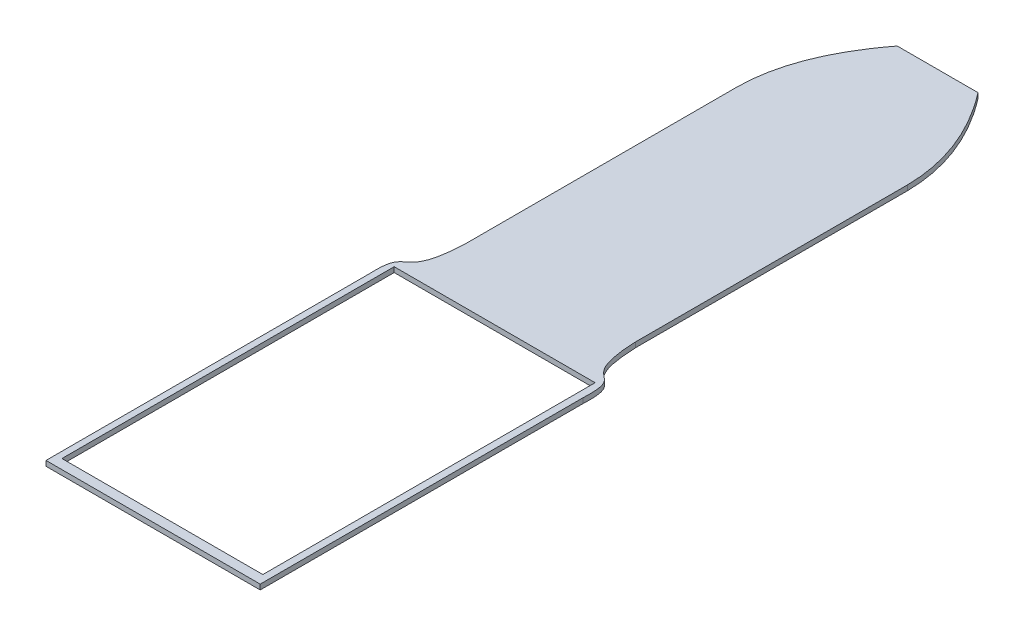
SolidWorks part; units mm, degrees
ref_plane "Front Plane" through (0, 0, 0) normal (0, 0, 1) x (1, 0, 0)
ref_plane "Top Plane" through (0, 0, 0) normal (0, 1, 0) x (1, 0, 0)
ref_plane "Right Plane" through (0, 0, 0) normal (1, 0, 0) x (0, 0, -1)
sketch "Sketch1" plane through (0, 0, 0) normal (0, -1, 0) x (-1, 0, 0)
  line L9 (-68.229, -80.901) -> (-68.229, 14.099)
  line L10 (-61.729, 35.9991) -> (-61.729, 115.9991)
  line L11 (-5.229, -80.901) -> (-5.229, 14.099)
  line L17 (-24.8578, 149.8289) -> (-48.6002, 149.8289)
  line L18 (-11.729, 35.9991) -> (-11.729, 115.9991)
  line L19 (-68.229, -80.901) -> (-5.229, -80.901)
  spline S0 degree 4 poles (-61.729, 35.9991) (-62.4215, 17.9336) (-67.5442, 25.0811) (-68.5403, 21.1592) (-68.229, 14.099) knots 0 0 0 0 0 1 1 1 1 1
  spline S1 degree 4 poles (-11.729, 35.9991) (-11.0365, 17.9336) (-5.9138, 25.0811) (-4.9177, 21.1592) (-5.229, 14.099) knots 0 0 0 0 0 1 1 1 1 1
  spline S2 degree 3 poles (-11.729, 115.9991) (-11.8683, 128.7119) (-17.3932, 140.1407) (-24.8578, 149.8289) knots 0 0 0 0 1 1 1 1
  spline S3 degree 3 poles (-61.729, 115.9991) (-61.5897, 128.7119) (-56.0648, 140.1407) (-48.6002, 149.8289) knots 0 0 0 0 1 1 1 1
  point P33 (-36.729, 149.8289)
  dimension "D1" = 95
  dimension "D2" = 80
extrude "Boss-Extrude1" add sketch "Sketch1" along normal blind 1.5 contours L11 S1 L18 S2 L17 S3 L10 S0 L9 L19
sketch "Sketch2" plane through (0, 0, 0) normal (0, 1, 0) x (1, 0, 0)
  line L0 (36.729, -80.901) -> (36.729, 149.8289) construction
  line L1 (68.229, -80.901) -> (5.229, -80.901) construction
  line L2 (24.8578, 149.8289) -> (48.6002, 149.8289) construction
  point P6 (0, 0)
ref_plane "Plane1" through (37.2492, 12.1282, -76.2334) normal (1, 0, 0) x (0, 0, -1)
ref_plane "Plane2" through (36.729, 0, 0) normal (1, 0, 0) x (0, 0, -1)
sketch "Sketch6" plane through (36.729, 0, 0) normal (1, 0, 0) x (0, 0, -1)
  line L0 (-311.9659, -1.5) -> (150.1639, -1.5) construction
  line L3 (-80.901, -1.5) -> (-80.901, -31.2379) construction
  line L4 (-80.901, -31.2379) -> (-59.344, -24.3435) construction
  line L5 (-59.344, -24.3435) -> (-3.1998, 14.8059) construction
  line L6 (-3.1998, 14.8059) -> (64.8448, -4.4458) construction
  line L7 (64.8448, -4.4458) -> (76.7941, -9.7566) construction
  line L8 (76.7941, -9.7566) -> (52.285, -33.2558) construction
  line L9 (52.285, -33.2558) -> (90.1548, -40.1862) construction
  line L10 (90.1548, -40.1862) -> (110.6986, -30.7806) construction
  line L11 (110.6986, -30.7806) -> (124.8069, -10.7319) construction
  line L12 (124.8069, -10.7319) -> (128.2424, -10.0885) construction
  line L13 (128.2424, -10.0885) -> (144.0541, -7.888) construction
  line L15 (144.0541, -7.888) -> (149.8289, -6.5571) construction
  line L17 (149.8289, -6.5571) -> (149.8289, -1.5) construction
  spline_without_curve S0
  spline S1 degree 2 poles (144.0541, -7.888) (149.8289, -6.5571) (149.8289, -1.5) knots 0 0 0 1 1 1
  point P2 (-66.6049, -16.7435)
  point P3 (15.6149, -9.0496)
  point P5 (94.0625, -25.8126)
  point P23 (-310.7247, -1.5)
  point P33 (-80.901, -1.5)
ref_plane "Plane3" through (0, 0, 66.6049) normal (0, 0, 1) x (1, 0, 0)
sketch "Sketch8" plane through (0, 0, 66.6049) normal (0, 0, 1) x (1, 0, 0)
  line L0 (5.229, -1.5) -> (5.229, -16.7435) construction
  line L1 (5.229, -16.7435) -> (36.729, -16.7435) construction
  line L2 (36.729, -31.7831) -> (36.729, 32.0033) construction
  spline S0 degree 2 poles (5.229, -1.5) (5.229, -16.7435) (36.729, -16.7435) knots 0 0 0 1 1 1
ref_plane "Plane4" through (0, 0, -15.6149) normal (0, 0, 1) x (1, 0, 0)
sketch "Sketch9" plane through (0, 0, -15.6149) normal (0, 0, 1) x (1, 0, 0)
  line L0 (5.1858, -1.5) -> (5.1858, -10.0945) construction
  line L1 (5.1858, -10.0945) -> (36.729, -9.0496) construction
  line L2 (36.6851, -19.5058) -> (36.6851, 6.741) construction
  spline S0 degree 2 poles (5.1858, -1.5) (5.1858, -10.0945) (36.729, -9.0496) knots 0 0 0 1 1 1
ref_plane "Plane5" through (0, 0, -94.0625) normal (0, 0, 1) x (1, 0, 0)
sketch "Sketch10" plane through (0, 0, -94.0625) normal (0, 0, 1) x (1, 0, 0)
  line L0 (11.729, -1.5) -> (11.729, -14.2215) construction
  line L1 (11.729, -14.2215) -> (19.3823, -27.1444) construction
  line L2 (19.3823, -27.1444) -> (28.5985, -23.3803) construction
  line L3 (28.5985, -23.3803) -> (26.9057, -25.8126) construction
  line L4 (26.9057, -25.8126) -> (36.729, -25.8126) construction
  line L5 (36.729, -63.5804) -> (36.729, 11.9552) construction
  spline_without_curve S0
  point P15 (36.729, -25.8126)
ref_plane "Plane6" through (0, 0, -144.0541) normal (0, 0, 1) x (1, 0, 0)
sketch "Sketch11" plane through (0, 0, -144.0541) normal (0, 0, 1) x (1, 0, 0)
  line L0 (36.729, 10.3711) -> (36.729, -26.1472) construction
  line L1 (20.7937, -1.5) -> (20.7937, -5.3294) construction
  line L2 (20.7937, -5.3294) -> (29.7132, -7.888) construction
  line L3 (29.7132, -7.888) -> (36.729, -7.888) construction
  spline S0 degree 3 poles (20.7937, -1.5) (20.7937, -5.3294) (29.7132, -7.888) (36.729, -7.888) knots 0 0 0 0 1 1 1 1
  point P8 (36.729, -7.888)
sketch3d "3DSketch1"
  line L0 (68.229, -1.5, 80.901) -> (68.229, -1.5, -14.099) construction
  line L1 (61.729, -1.5, -35.9991) -> (61.729, -1.5, -115.9991) construction
  line L2 (68.229, -1.5, 80.901) -> (68.229, -1.5, -14.099)
  line L3 (61.729, -1.5, -35.9991) -> (61.729, -1.5, -115.9991)
  line L10 (68.229, -1.5, 80.901) -> (5.229, -1.5, 80.901)
  line L11 (5.229, -1.5, 80.901) -> (5.229, -1.5, -14.099)
  line L12 (11.729, -1.5, -35.9991) -> (11.729, -1.5, -115.9991)
  line L13 (24.8578, -1.5, -149.8289) -> (48.6002, -1.5, -149.8289)
  line L14 (61.729, -1.5, -115.9991) -> (61.729, -1.5, -35.9991)
  line L15 (68.229, -1.5, -14.099) -> (68.229, -1.5, 80.901)
  line L16 (68.229, -1.5, 80.901) -> (5.229, -1.5, 80.901)
  line L17 (5.229, -1.5, 80.901) -> (5.229, -1.5, -14.099)
  line L18 (11.729, -1.5, -35.9991) -> (11.729, -1.5, -115.9991)
  line L19 (24.8578, -1.5, -149.8289) -> (48.6002, -1.5, -149.8289)
  line L20 (61.729, -1.5, -115.9991) -> (61.729, -1.5, -35.9991)
  line L21 (68.229, -1.5, -14.099) -> (68.229, -1.5, 80.901)
  spline S0 degree 4 poles (468.0697, -1.5, -1994.0017) (-453.2843, -1.5, 2081.7908) (645.5202, -1.5, -2220.6502) (-511.1273, -1.5, 2159.6181) (607.0904, -1.5, -1940.0141) knots -1.808869 -1.808869 -1.808869 -1.808869 -1.808869 3.465781 3.465781 3.465781 3.465781 3.465781 only from (61.729, -1.5, -35.9991) to (68.229, -1.5, -14.099) construction
  spline S1 degree 3 poles (-1906.7427, -1.5, 183.0585) (2270.6206, -1.5, 40.3865) (-2202.6608, -1.5, -662.5315) (1980.4043, -1.5, 367.2322) knots -6.996975 -6.996975 -6.996975 -6.996975 10.128451 10.128451 10.128451 10.128451 only from (61.729, -1.5, -115.9991) to (48.6002, -1.5, -149.8289) construction
  spline S2 degree 4 poles (61.729, -1.5, -35.9991) (62.4215, -1.5, -17.9336) (67.5442, -1.5, -25.0811) (68.5403, -1.5, -21.1592) (68.229, -1.5, -14.099) knots 0 0 0 0 0 1 1 1 1 1
  spline S3 degree 3 poles (61.729, -1.5, -115.9991) (61.5897, -1.5, -128.7119) (56.0648, -1.5, -140.1407) (48.6002, -1.5, -149.8289) knots 0 0 0 0 1 1 1 1
  spline S8 degree 4 poles (-533.6502, -1.5, -1940.0792) (584.5986, -1.5, 2159.6683) (-572.0699, -1.5, -2220.6803) (526.7444, -1.5, 2081.8011) (-394.61, -1.5, -1993.9942) knots -2.465802 -2.465802 -2.465802 -2.465802 -2.465802 2.808867 2.808867 2.808867 2.808867 2.808867 only from (5.229, -1.5, -14.099) to (11.729, -1.5, -35.9991)
  spline S9 degree 3 poles (1980.2007, -1.5, 183.0585) (-2197.1626, -1.5, 40.3865) (2276.1188, -1.5, -662.5315) (-1906.9463, -1.5, 367.2322) knots -6.996975 -6.996975 -6.996975 -6.996975 10.128451 10.128451 10.128451 10.128451 only from (11.729, -1.5, -115.9991) to (24.8578, -1.5, -149.8289)
  spline S10 degree 3 poles (1980.3898, -1.5, 367.2286) (-2202.6237, -1.5, -662.5233) (2270.5585, -1.5, 40.3777) (-1906.6625, -1.5, 183.0557) knots -9.128431 -9.128431 -9.128431 -9.128431 7.996865 7.996865 7.996865 7.996865 only from (48.6002, -1.5, -149.8289) to (61.729, -1.5, -115.9991)
  spline S11 degree 4 poles (468.0697, -1.5, -1994.0017) (-453.2843, -1.5, 2081.7908) (645.5202, -1.5, -2220.6502) (-511.1273, -1.5, 2159.6181) (607.0904, -1.5, -1940.0141) knots -1.808869 -1.808869 -1.808869 -1.808869 -1.808869 3.465781 3.465781 3.465781 3.465781 3.465781 only from (61.729, -1.5, -35.9991) to (68.229, -1.5, -14.099)
  spline S12 degree 4 poles (5.229, -1.5, -14.099) (4.9177, -1.5, -21.1592) (5.9138, -1.5, -25.0811) (11.0365, -1.5, -17.9336) (11.729, -1.5, -35.9991) knots 0 0 0 0 0 1 1 1 1 1
  spline S13 degree 3 poles (11.729, -1.5, -115.9991) (11.8683, -1.5, -128.7119) (17.3932, -1.5, -140.1407) (24.8578, -1.5, -149.8289) knots 0 0 0 0 1 1 1 1
  spline S14 degree 3 poles (48.6002, -1.5, -149.8289) (56.0648, -1.5, -140.1407) (61.5897, -1.5, -128.7119) (61.729, -1.5, -115.9991) knots 0 0 0 0 1 1 1 1
  spline S15 degree 4 poles (61.729, -1.5, -35.9991) (62.4215, -1.5, -17.9336) (67.5442, -1.5, -25.0811) (68.5403, -1.5, -21.1592) (68.229, -1.5, -14.099) knots 0 0 0 0 0 1 1 1 1 1
  dimension "D1" = 0
sketch "Sketch13" plane through (0, -1.5, 0) normal (0, -1, 0) x (1, 0, 0)
other "Boundary-Surface3"
ref_plane "Plane7" through (36.729, 0, 0) normal (1, 0, 0) x (0, 0, -1)
mirror "Mirror1" about plane through (36.729, 0, 0) normal (1, 0, 0) of bodies 104
sketch "Sketch17" plane through (0, 0, 0) normal (0, 1, 0) x (1, 0, 0)
  line L1 (7.0866, 19.6424) -> (66.1822, 19.6424)
  line L2 (7.0866, 19.6424) -> (7.0866, -78.0766)
  line L3 (7.0866, -78.0766) -> (66.1822, -78.0766)
  line L4 (66.1822, 19.6424) -> (66.1822, -78.0766)
extrude "Cut-Extrude2" cut sketch "Sketch17" against normal through all
